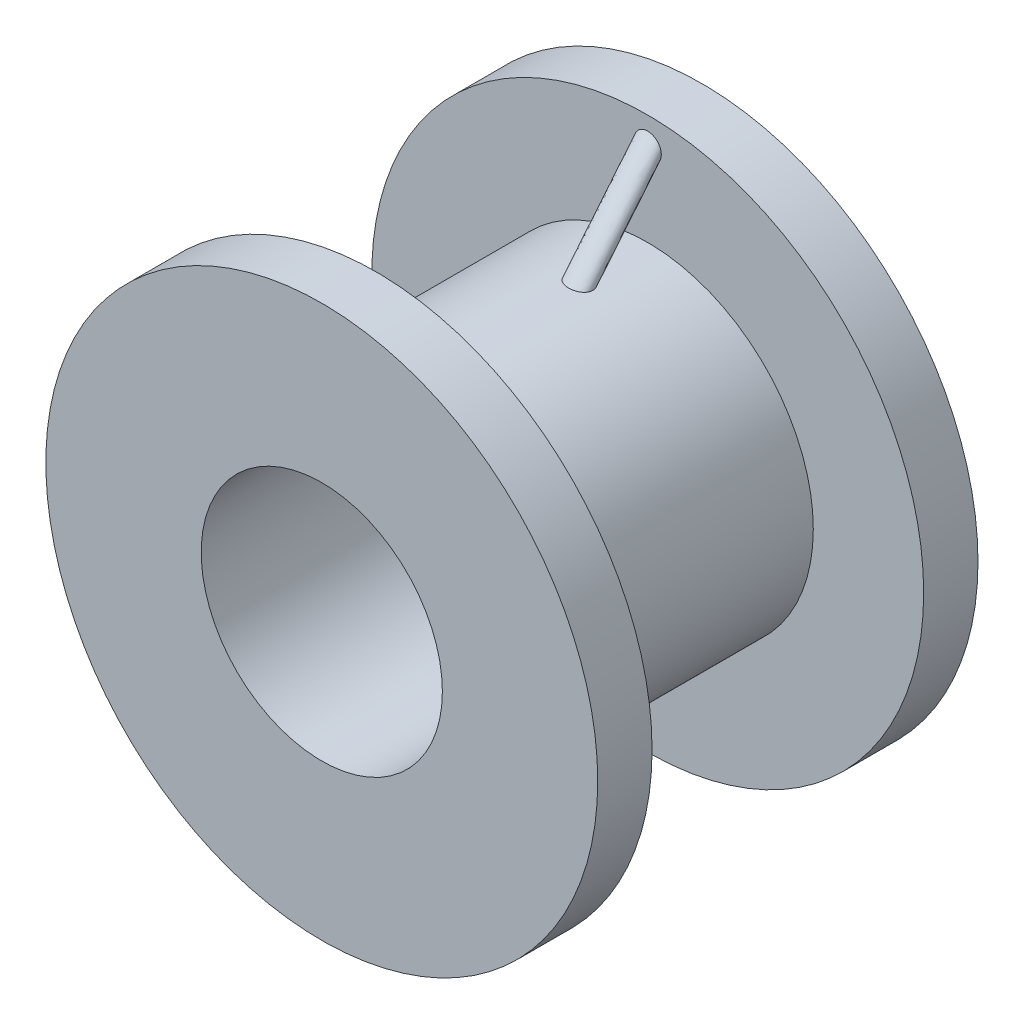
SolidWorks part; units mm, degrees
ref_plane "Front Plane" through (0, 0, 0) normal (0, 0, 1) x (1, 0, 0)
ref_plane "Top Plane" through (0, 0, 0) normal (0, 1, 0) x (1, 0, 0)
ref_plane "Right Plane" through (0, 0, 0) normal (1, 0, 0) x (0, 0, -1)
sketch "Sketch1" plane through (0, 0, 0) normal (0, 0, 1) x (1, 0, 0)
  circle A0 centre (0, 0) radius 15.24
  circle A1 centre (0, 0) radius 11.1
extrude "Boss-Extrude1" add sketch "Sketch1" along normal blind 30
sketch "Sketch3" plane through (0, 0, 0) normal (0, 0, 1) x (1, 0, 0)
  circle A0 centre (0, 0) radius 25.4
  circle A2 centre (0, 0) radius 5.1
  circle A3 centre (0, 8) radius 1.5
  circle A4 centre (8, 0) radius 1.5
  circle A5 centre (0, -8) radius 1.5
  circle A6 centre (-8, 0) radius 1.5
  dimension "D1" = 4
extrude "Boss-Extrude2" add sketch "Sketch3" along normal blind 5
sketch "Sketch4" plane through (0, 0, 30) normal (0, 0, 1) x (1, 0, 0)
  circle A0 centre (0, 0) radius 25.4
  circle A1 centre (0, 0) radius 11.1
extrude "Boss-Extrude3" add sketch "Sketch4" along normal blind 5
sketch "Sketch5" plane through (0, 0, 0) normal (0, 0, -1) x (-1, 0, 0)
  circle A0 centre (0, 0) radius 11.1
extrude "Cut-Extrude1" cut sketch "Sketch5" against normal blind 1.2
sketch "Sketch10" plane through (0, 0, 5) normal (0, 0, 1) x (1, 0, 0)
  circle A2 centre (0, 22.86) radius 1.25
sketch "Sketch14" plane through (0, 0, 0) normal (1, 0, 0) x (0, 0, -1)
  line L1 (-5, 24.11) -> (-5, 21.61) construction
  line L3 (-5, 22.86) -> (-12.9883, 13.1206)
  point P1 (0, 0)
sweep "Sweep3" add profiles "Sketch10" path "Sketch14"
